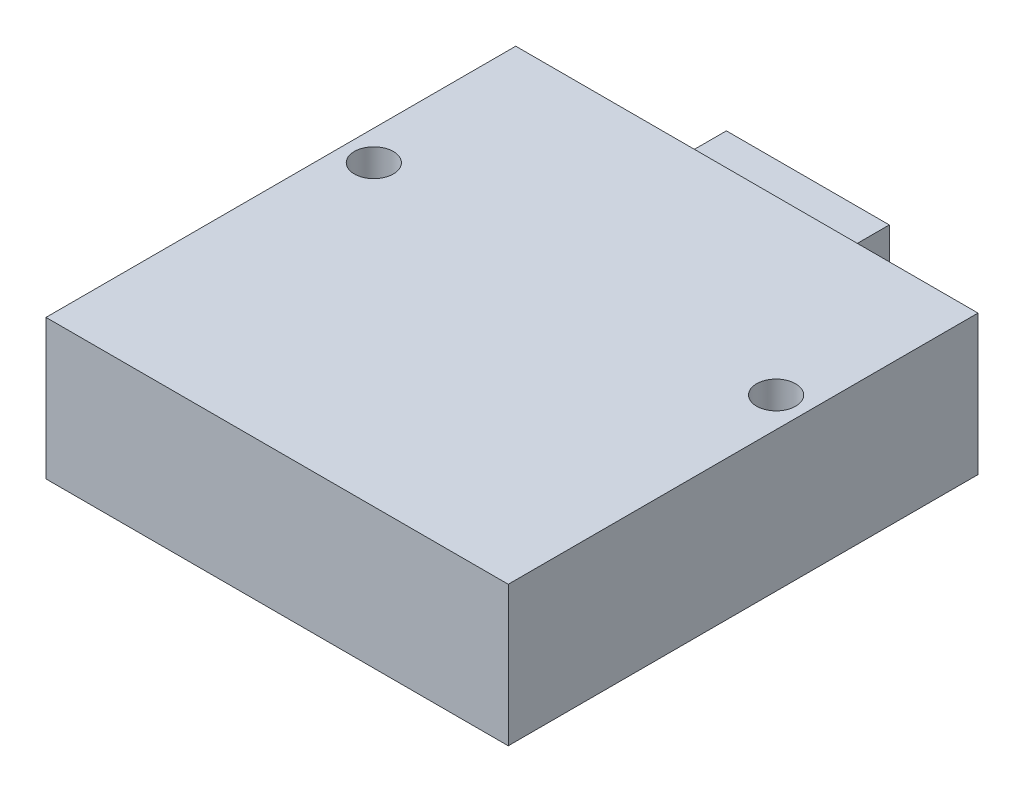
SolidWorks part; units mm, degrees
ref_plane "Front Plane" through (0, 0, 0) normal (0, 0, 1) x (1, 0, 0)
ref_plane "Top Plane" through (0, 0, 0) normal (0, 1, 0) x (1, 0, 0)
ref_plane "Right Plane" through (0, 0, 0) normal (1, 0, 0) x (0, 0, -1)
sketch "Sketch1" plane through (0, 0, 0) normal (0, 0, 1) x (1, 0, 0)
  line L1 (-58.7375, -17.78) -> (58.7375, -17.78)
  line L2 (-58.7375, -17.78) -> (-58.7375, 17.78)
  line L3 (-58.7375, 17.78) -> (58.7375, 17.78)
  line L4 (58.7375, -17.78) -> (58.7375, 17.78)
  line L5 (-58.7375, -17.78) -> (58.7375, 17.78) construction
  line L6 (-58.7375, 17.78) -> (58.7375, -17.78) construction
  point P0 (0, 0)
  dimension "D1" = 117.475
  dimension "D2" = 35.56
extrude "Extrude1" add sketch "Sketch1" along normal blind 119.38
sketch "Sketch2" plane through (0, 0, 0) normal (0, 0, -1) x (-1, 0, 0)
  line L1 (-20.701, -10.414) -> (20.701, -10.414)
  line L2 (-20.701, -10.414) -> (-20.701, 10.414)
  line L3 (-20.701, 10.414) -> (20.701, 10.414)
  line L4 (20.701, -10.414) -> (20.701, 10.414)
  line L5 (-20.701, -10.414) -> (20.701, 10.414) construction
  line L6 (-20.701, 10.414) -> (20.701, -10.414) construction
  point P0 (0, 0)
  dimension "D1" = 20.828
  dimension "D2" = 41.402
extrude "Extrude2" add sketch "Sketch2" along normal blind 15.494
sketch "Sketch3" plane through (0, -17.78, 0) normal (0, -1, 0) x (1, 0, 0)
  line L0 (-51.1175, 0) -> (-51.1175, 43.688) construction
  line L1 (-58.7375, 0) -> (58.7375, 0) construction
  line L2 (-51.1175, 43.688) -> (-58.7375, 43.688) construction
  line L3 (-58.7375, 119.38) -> (-58.7375, 0) construction
  line L4 (51.1175, 0) -> (51.1175, 43.688) construction
  line L5 (51.1175, 43.688) -> (58.7375, 43.688) construction
  line L6 (58.7375, 119.38) -> (58.7375, 0) construction
  dimension "D1" = 43.688
  dimension "D2" = 7.62
hole_wizard "25/64 (0.39063) Diameter Hole1" positions "3DSketch1" profile "Sketch5" hole size "25/64" standard "Ansi Inch" end condition through all
sketch3d "3DSketch1"
  point P0 (-51.1175, -17.78, 43.688)
  point P3 (51.1175, -17.78, 43.688)
sketch "Sketch5" plane through (-51.1175, -17.78, 43.688) normal (1, 0, 0) x (0, 0, -1)
  line L0 (0, 0) -> (0, 35.56)
  line L1 (0, 35.56) -> (4.961, 35.56)
  line L2 (4.961, 35.56) -> (4.961, 0)
  line L5 (4.961, 0) -> (0, 0)
  line L11 (0, -6.35) -> (0, 107.95) construction
  dimension "Thru Hole Dia." = 9.922
  dimension "Thru Hole Depth" = 35.56
sketch "Sketch6" plane through (0, 0, -15.494) normal (0, 0, -1) x (-1, 0, 0)
  point P0 (0, 0)
sketch "Sketch7" plane through (0, 0, 119.38) normal (0, 0, 1) x (1, 0, 0)
  point P0 (0, 0)
